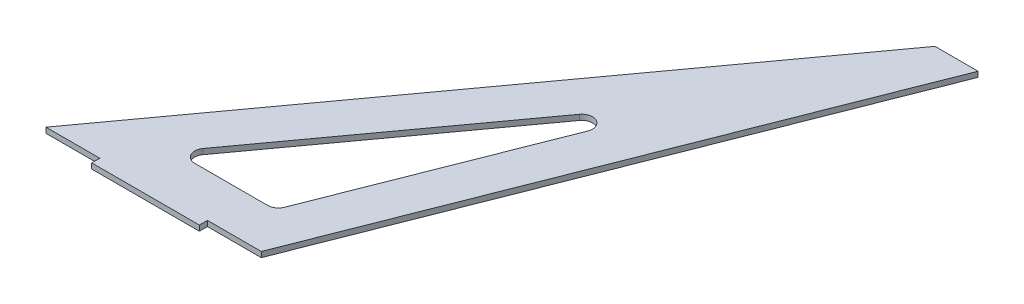
SolidWorks part; units mm, degrees
material "Balsa"
ref_plane "Front Plane" through (0, 0, 0) normal (0, 0, 1) x (1, 0, 0)
ref_plane "Top Plane" through (0, 0, 0) normal (0, 1, 0) x (1, 0, 0)
ref_plane "Right Plane" through (0, 0, 0) normal (1, 0, 0) x (0, 0, -1)
sketch "Sketch1" plane through (0, 0, 0) normal (0, 1, 0) x (1, 0, 0)
  line L0 (0, 0) -> (0, -279.2704) construction
  line L1 (0, 0) -> (387.4796, 0) construction
  line L2 (-119.3254, 0) -> (-246.3254, 0)
  line L3 (-246.3254, 0) -> (-25.4, 303.5229)
  line L4 (-25.4, 303.5229) -> (0, 303.5229)
  line L5 (0, 303.5229) -> (-119.3254, 0)
  dimension "D1" = 127
  dimension "D2" = 25.4
  dimension "D3" = 326.136
  dimension "D4" = 375.412
extrude "Boss-Extrude1" add sketch "Sketch1" along normal blind 3.175
sketch "Sketch2" plane through (0, 3.175, 0) normal (0, 1, 0) x (1, 0, 0)
  line L8 (-136.6321, 25.4) -> (-66.4117, 204.0166)
  line L9 (-66.4117, 204.0166) -> (-196.4215, 25.4)
  line L10 (-196.4215, 25.4) -> (-136.6321, 25.4)
  line L11 (-136.6321, 25.4) -> (-66.4117, 204.0166)
  line L12 (-66.4117, 204.0166) -> (-196.4215, 25.4)
  line L13 (-196.4215, 25.4) -> (-136.6321, 25.4)
  dimension "D1" = 25.4
extrude "Cut-Extrude1" cut sketch "Sketch2" against normal blind 3.175
fillet "Fillet1" radius 6.35 3 edges at (-136.6321, 1.5875, -25.4) (-196.4215, 1.5875, -25.4) (-66.4117, 1.5875, -204.0166)
sketch "Sketch3" plane through (0, 0, 0) normal (0, 0, 1) x (1, 0, 0)
  line L0 (-182.8254, 3.175) -> (-182.8254, 0) construction
  line L1 (-246.3254, 3.175) -> (-119.3254, 3.175) construction
  line L2 (-246.3254, 0) -> (-119.3254, 0) construction
  line L4 (-214.5754, 3.175) -> (-151.0754, 3.175)
  line L5 (-214.5754, 3.175) -> (-214.5754, 0)
  line L6 (-214.5754, 0) -> (-151.0754, 0)
  line L7 (-151.0754, 3.175) -> (-151.0754, 0)
  line L8 (-214.5754, 3.175) -> (-151.0754, 0) construction
  line L9 (-214.5754, 0) -> (-151.0754, 3.175) construction
  point P6 (-182.8254, 1.5875)
  dimension "D1" = 63.5
extrude "Boss-Extrude2" add sketch "Sketch3" along normal blind 4.7625
